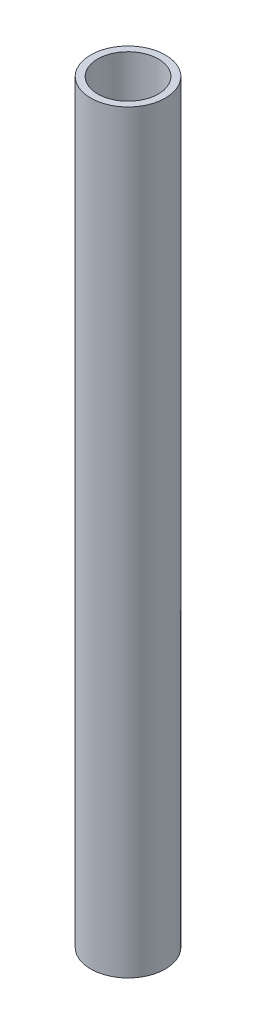
SolidWorks part; units mm, degrees
material "СТ3КП"
ref_plane "Спереди" through (0, 0, 0) normal (0, 0, 1) x (1, 0, 0)
ref_plane "Сверху" through (0, 0, 0) normal (0, 1, 0) x (1, 0, 0)
ref_plane "Справа" through (0, 0, 0) normal (1, 0, 0) x (0, 0, -1)
sketch "Эскиз1" plane through (0, 0, 0) normal (0, 1, 0) x (1, 0, 0)
  line L0 (0, 200914.2922) -> (0, -249007.8193) construction
  line L1 (-130, 9.15) -> (130, 9.15) construction
  point P0 (0, 0)
  circle B0 centre (0, -1.5) radius 8.65
  circle B1 centre (0, -1.5) radius 10.65
sketch_block_instance "Труба 21_3х2 1_2-1"
sketch_block "Труба 21_3х2 1_2" parameters "D2"=21.3, "D1"=2
extrude "Бобышка-Вытянуть1" add sketch "Эскиз1" along normal up to vertex (215 mm away)
